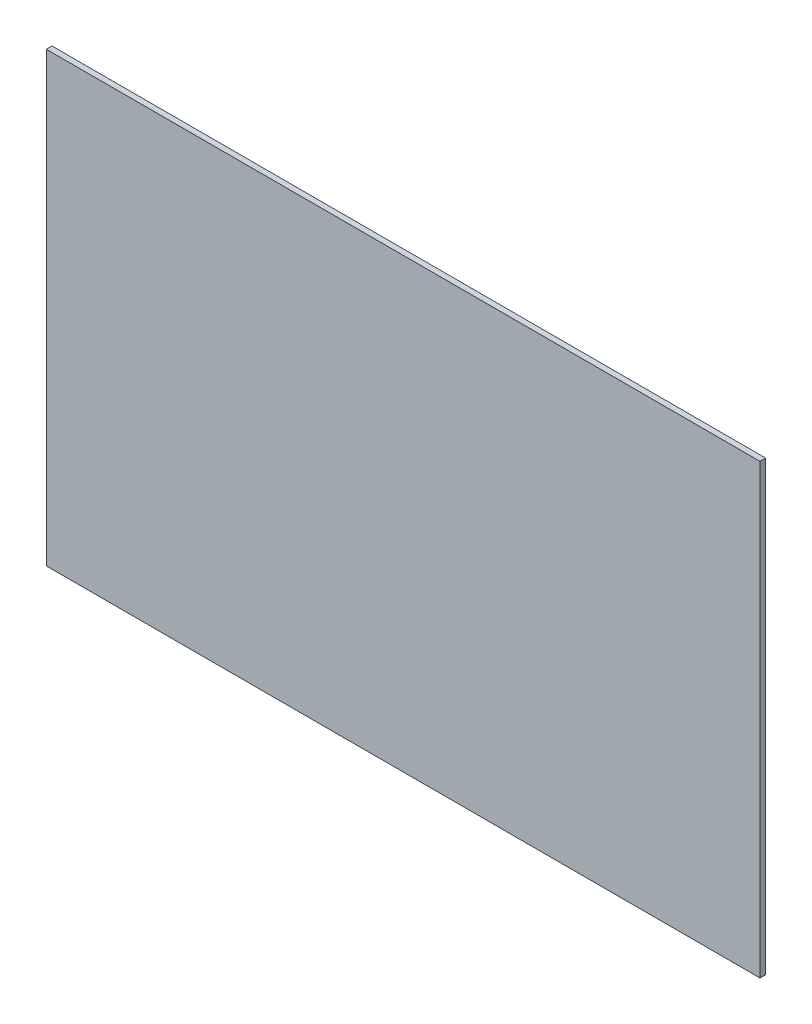
SolidWorks part; units mm, degrees
material "Perspex (TM) GS Acrylic Cast Sheet"
ref_plane "Front Plane" through (0, 0, 0) normal (0, 0, 1) x (1, 0, 0)
ref_plane "Top Plane" through (0, 0, 0) normal (0, 1, 0) x (1, 0, 0)
ref_plane "Right Plane" through (0, 0, 0) normal (1, 0, 0) x (0, 0, -1)
sketch "Sketch1" plane through (0, 0, 0) normal (0, 0, 1) x (1, 0, 0)
  line L1 (400.05, 250.825) -> (-400.05, 250.825)
  line L2 (400.05, 250.825) -> (400.05, -250.825)
  line L3 (400.05, -250.825) -> (-400.05, -250.825)
  line L4 (-400.05, 250.825) -> (-400.05, -250.825)
  line L5 (400.05, 250.825) -> (-400.05, -250.825) construction
  line L6 (400.05, -250.825) -> (-400.05, 250.825) construction
  point P0 (0, 0)
  dimension "D1" = 800.1
  dimension "D2" = 501.65
extrude "Boss-Extrude1" add sketch "Sketch1" along normal blind 6.35
